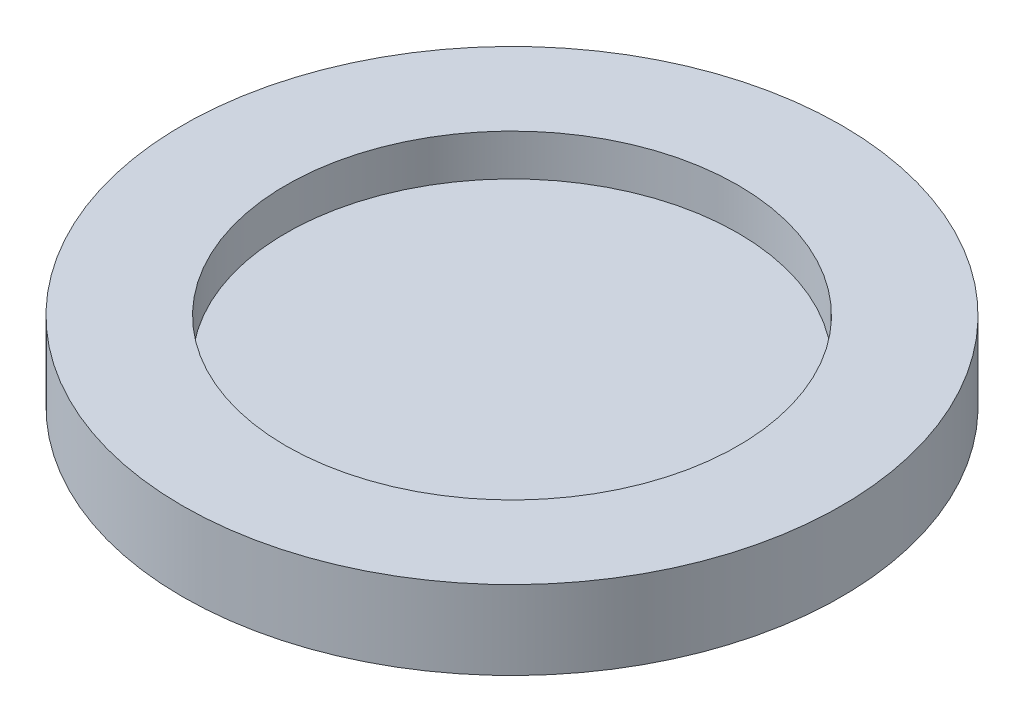
SolidWorks part; units mm, degrees
ref_plane "Plan de face" through (0, 0, 0) normal (0, 0, 1) x (1, 0, 0)
ref_plane "Plan de dessus" through (0, 0, 0) normal (0, 1, 0) x (1, 0, 0)
ref_plane "Plan de droite" through (0, 0, 0) normal (1, 0, 0) x (0, 0, -1)
sketch "Esquisse1" plane through (0, 0, 0) normal (0, 1, 0) x (1, 0, 0)
  circle A0 centre (0, 0) radius 7.95
  circle A1 centre (0, 0) radius 5.45
  dimension "D1" = 15.9
  dimension "D2" = 10.9
extrude "Boss.-Extru.1" add sketch "Esquisse1" along normal blind 1.9
sketch "Esquisse3" plane through (0, 0, 0) normal (0, 1, 0) x (1, 0, 0)
  circle A0 centre (0, 0) radius 5.45
extrude "Boss.-Extru.2" add sketch "Esquisse3" along normal blind 0.9
